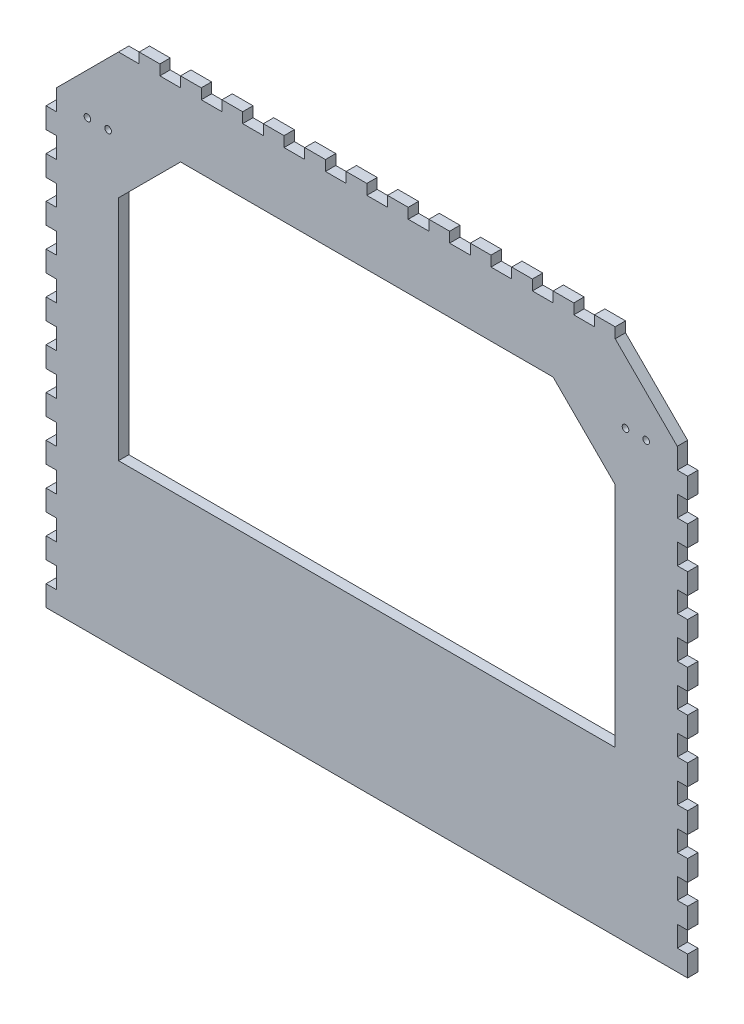
SolidWorks part; units mm, degrees
material "Buche"
ref_plane "Ebene vorne" through (0, 0, 0) normal (0, 0, 1) x (1, 0, 0)
ref_plane "Ebene oben" through (0, 0, 0) normal (0, 1, 0) x (1, 0, 0)
ref_plane "Ebene rechts" through (0, 0, 0) normal (1, 0, 0) x (0, 0, -1)
sketch "Skizze1" plane through (0, 0, 0) normal (0, 0, 1) x (1, 0, 0)
  line L0 (5, 10) -> (5, 20)
  line L1 (5, 0) -> (305, 0)
  line L2 (305, 10) -> (305, 20)
  line L3 (55, 250) -> (65, 250)
  line L4 (5, 220) -> (35, 250)
  line L5 (305, 220) -> (275, 250)
  line L6 (275, 188.9712) -> (245, 218.9712)
  line L7 (35, 78.9712) -> (275, 78.9712)
  line L8 (35, 78.9712) -> (35, 188.9712)
  line L9 (65, 218.9712) -> (245, 218.9712)
  line L10 (275, 78.9712) -> (275, 188.9712)
  line L11 (35, 188.9712) -> (65, 218.9712)
  line L12 (35, 250) -> (45, 250)
  line L13 (305, 0) -> (310, 0)
  line L14 (310, 0) -> (310, 10)
  line L15 (310, 10) -> (305, 10)
  line L16 (305, 30) -> (305, 40)
  line L17 (305, 20) -> (310, 20)
  line L18 (310, 20) -> (310, 30)
  line L19 (310, 30) -> (305, 30)
  line L20 (305, 50) -> (305, 60)
  line L21 (305, 40) -> (310, 40)
  line L22 (310, 40) -> (310, 50)
  line L23 (310, 50) -> (305, 50)
  line L24 (305, 70) -> (305, 80)
  line L25 (305, 60) -> (310, 60)
  line L26 (310, 60) -> (310, 70)
  line L27 (310, 70) -> (305, 70)
  line L28 (305, 90) -> (305, 100)
  line L29 (305, 80) -> (310, 80)
  line L30 (310, 80) -> (310, 90)
  line L31 (310, 90) -> (305, 90)
  line L32 (305, 110) -> (305, 120)
  line L33 (305, 100) -> (310, 100)
  line L34 (310, 100) -> (310, 110)
  line L35 (310, 110) -> (305, 110)
  line L36 (305, 130) -> (305, 140)
  line L37 (305, 120) -> (310, 120)
  line L38 (310, 120) -> (310, 130)
  line L39 (310, 130) -> (305, 130)
  line L40 (305, 150) -> (305, 160)
  line L41 (305, 140) -> (310, 140)
  line L42 (310, 140) -> (310, 150)
  line L43 (310, 150) -> (305, 150)
  line L44 (305, 170) -> (305, 180)
  line L45 (305, 160) -> (310, 160)
  line L46 (310, 160) -> (310, 170)
  line L47 (310, 170) -> (305, 170)
  line L48 (305, 190) -> (305, 200)
  line L49 (305, 180) -> (310, 180)
  line L50 (310, 180) -> (310, 190)
  line L51 (310, 190) -> (305, 190)
  line L52 (305, 210) -> (305, 220)
  line L53 (305, 200) -> (310, 200)
  line L54 (310, 200) -> (310, 210)
  line L55 (310, 210) -> (305, 210)
  line L56 (5, 0) -> (0, 0)
  line L57 (0, 0) -> (0, 10)
  line L58 (0, 10) -> (5, 10)
  line L59 (5, 30) -> (5, 40)
  line L60 (0, 20) -> (0, 30)
  line L61 (0, 30) -> (5, 30)
  line L62 (5, 50) -> (5, 60)
  line L63 (0, 40) -> (0, 50)
  line L64 (0, 50) -> (5, 50)
  line L65 (5, 70) -> (5, 80)
  line L66 (0, 60) -> (0, 70)
  line L67 (0, 70) -> (5, 70)
  line L68 (5, 90) -> (5, 100)
  line L69 (0, 80) -> (0, 90)
  line L70 (0, 90) -> (5, 90)
  line L71 (5, 110) -> (5, 120)
  line L72 (0, 100) -> (0, 110)
  line L73 (0, 110) -> (5, 110)
  line L74 (5, 130) -> (5, 140)
  line L75 (0, 120) -> (0, 130)
  line L76 (0, 130) -> (5, 130)
  line L77 (5, 150) -> (5, 160)
  line L78 (0, 140) -> (0, 150)
  line L79 (0, 150) -> (5, 150)
  line L80 (5, 170) -> (5, 180)
  line L81 (0, 160) -> (0, 170)
  line L82 (0, 170) -> (5, 170)
  line L83 (5, 190) -> (5, 200)
  line L84 (0, 180) -> (0, 190)
  line L85 (0, 190) -> (5, 190)
  line L86 (5, 210) -> (5, 220)
  line L87 (0, 200) -> (0, 210)
  line L88 (0, 210) -> (5, 210)
  line L89 (0, 20) -> (5, 20)
  line L90 (0, 40) -> (5, 40)
  line L91 (0, 60) -> (5, 60)
  line L92 (0, 80) -> (5, 80)
  line L93 (0, 100) -> (5, 100)
  line L94 (0, 120) -> (5, 120)
  line L95 (0, 140) -> (5, 140)
  line L96 (0, 160) -> (5, 160)
  line L97 (0, 180) -> (5, 180)
  line L98 (0, 200) -> (5, 200)
  line L99 (45, 250) -> (45, 255)
  line L100 (45, 255) -> (55, 255)
  line L101 (55, 255) -> (55, 250)
  line L102 (65, 250) -> (65, 255)
  line L103 (65, 255) -> (75, 255)
  line L104 (75, 255) -> (75, 250)
  line L105 (75, 250) -> (85, 250)
  line L106 (85, 250) -> (85, 255)
  line L107 (85, 255) -> (95, 255)
  line L108 (95, 255) -> (95, 250)
  line L109 (95, 250) -> (105, 250)
  line L110 (105, 250) -> (105, 255)
  line L111 (105, 255) -> (115, 255)
  line L112 (115, 255) -> (115, 250)
  line L113 (115, 250) -> (125, 250)
  line L114 (125, 250) -> (125, 255)
  line L115 (125, 255) -> (135, 255)
  line L116 (135, 255) -> (135, 250)
  line L117 (135, 250) -> (145, 250)
  line L118 (145, 250) -> (145, 255)
  line L119 (145, 255) -> (155, 255)
  line L120 (155, 255) -> (155, 250)
  line L121 (155, 250) -> (165, 250)
  line L122 (165, 250) -> (165, 255)
  line L123 (165, 255) -> (175, 255)
  line L124 (175, 255) -> (175, 250)
  line L125 (175, 250) -> (185, 250)
  line L126 (185, 250) -> (185, 255)
  line L127 (185, 255) -> (195, 255)
  line L128 (195, 255) -> (195, 250)
  line L129 (195, 250) -> (205, 250)
  line L130 (205, 250) -> (205, 255)
  line L131 (205, 255) -> (215, 255)
  line L132 (215, 255) -> (215, 250)
  line L133 (215, 250) -> (225, 250)
  line L134 (225, 250) -> (225, 255)
  line L135 (225, 255) -> (235, 255)
  line L136 (235, 255) -> (235, 250)
  line L137 (235, 250) -> (245, 250)
  line L138 (245, 250) -> (245, 255)
  line L139 (245, 255) -> (255, 255)
  line L140 (255, 255) -> (255, 250)
  line L141 (255, 250) -> (265, 250)
  line L142 (265, 250) -> (265, 255)
  line L143 (265, 255) -> (275, 255)
  line L144 (275, 255) -> (275, 250)
  circle A0 centre (290, 215) radius 1.6
  circle A1 centre (280, 215) radius 1.6
  circle A2 centre (20, 215) radius 1.6
  circle A3 centre (30, 215) radius 1.6
  dimension "D1" = 12
extrude "Aufsatz-Linear austragen1" add sketch "Skizze1" along normal blind 5
